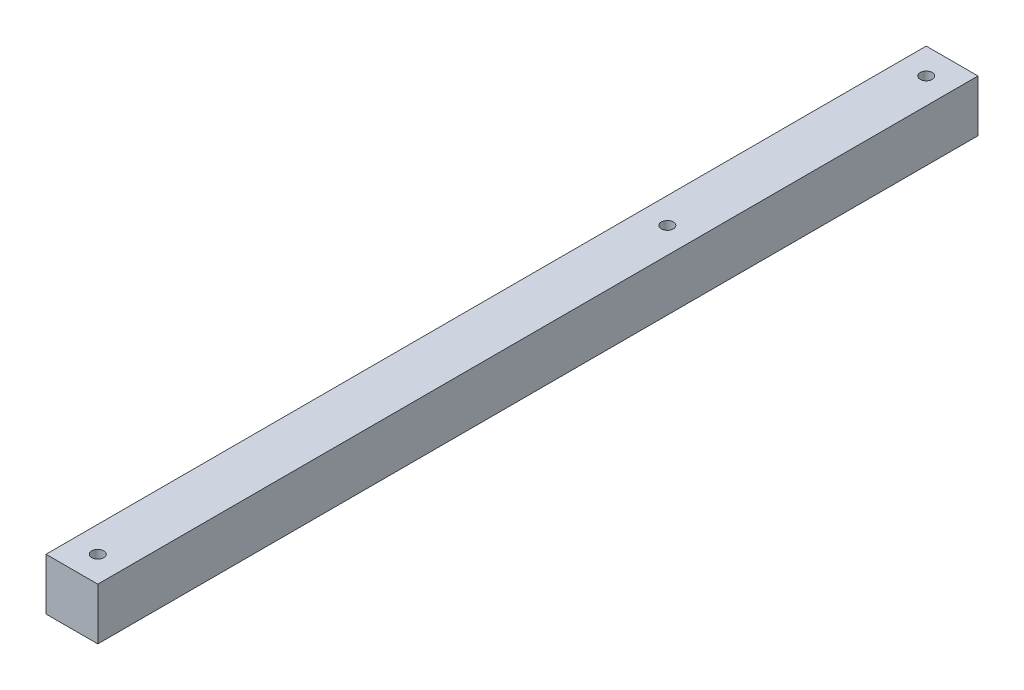
SolidWorks part; units mm, degrees
ref_plane "Front" through (0, 0, 0) normal (0, 0, 1) x (1, 0, 0)
ref_plane "Top" through (0, 0, 0) normal (0, 1, 0) x (1, 0, 0)
ref_plane "Right" through (0, 0, 0) normal (1, 0, 0) x (0, 0, -1)
sketch "Sketch18" plane through (0, 0, 0) normal (0, 1, 0) x (1, 0, 0)
  line L1 (-12.7, -12.7) -> (0, -12.7)
  line L2 (-12.7, -12.7) -> (-12.7, 203.2)
  line L3 (-12.7, 203.2) -> (0, 203.2)
  line L4 (0, -12.7) -> (0, 203.2)
  dimension "D1" = 12.7
  dimension "D2" = 12.7
  dimension "D3" = 12.7
  dimension "D4" = 215.9
extrude "Boss-Extrude3" add sketch "Sketch18" along normal blind 12.7
sketch "Sketch26" plane through (0, 12.7, 0) normal (0, 1, 0) x (1, 0, 0)
  line L0 (-6.35, -12.7) -> (-6.35, 203.2) construction
  line L1 (-12.7, -12.7) -> (0, -12.7) construction
  line L2 (0, 203.2) -> (-12.7, 203.2) construction
  point P6 (-6.35, 196.85)
  point P7 (-6.35, -6.35)
  point P8 (-6.35, 133.35)
  dimension "D1" = 6.35
  dimension "D2" = 6.35
  dimension "D3" = 63.5
hole_wizard "#32 (0.116) Diameter Hole7" positions "Sketch27" profile "Sketch28" hole size "#32" standard "ANSI Inch" end condition through all
sketch "Sketch27" plane through (0, 12.7, 0) normal (0, 1, 0) x (1, 0, 0)
  point P0 (-6.35, 196.85)
  point P3 (-6.35, 133.35)
  point P6 (-6.35, -6.35)
sketch "Sketch28" plane through (-6.35, 12.7, -196.85) normal (1, 0, 0) x (0, 0, 1)
  line L0 (0, 0) -> (0, 12.7)
  line L1 (0, 12.7) -> (1.4732, 12.7)
  line L2 (1.4732, 12.7) -> (1.4732, 0)
  line L5 (1.4732, 0) -> (0, 0)
  line L11 (0, -6.35) -> (0, 107.95) construction
  dimension "Thru Hole Dia." = 2.9464
  dimension "Thru Hole Depth" = 12.7
sketch "Sketch29" plane through (0, 0, 0) normal (1, 0, 0) x (0, 0, -1)
  line L0 (-12.7, 0) -> (203.2, 0) construction
  line L1 (144.78, 0) -> (151.13, 0)
  line L2 (144.78, 0) -> (144.78, 12.7)
  line L3 (144.78, 12.7) -> (151.13, 12.7)
  line L4 (151.13, 0) -> (151.13, 12.7)
  line L5 (-12.7, 12.7) -> (203.2, 12.7) construction
  line L6 (203.2, 12.7) -> (203.2, 0) construction
  point P10 (203.2, 6.35)
  dimension "D1" = 58.42
  dimension "D2" = 6.35
